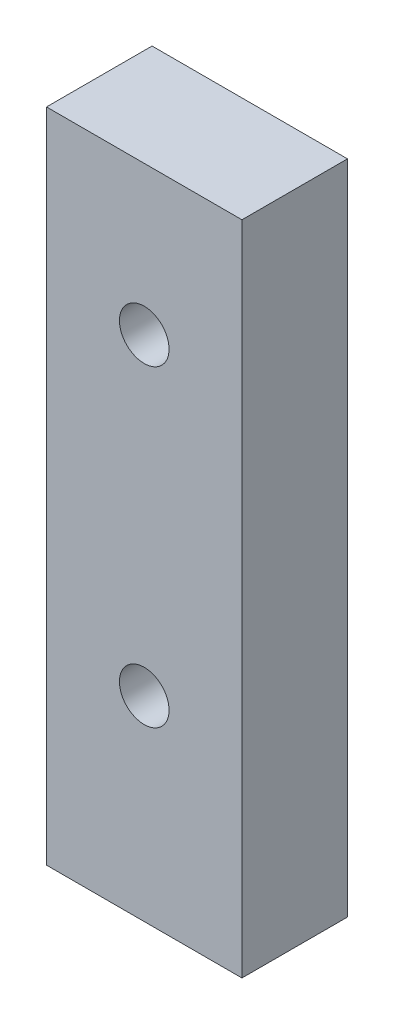
SolidWorks part; units mm, degrees
ref_plane "Alzado" through (0, 0, 0) normal (0, 0, 1) x (1, 0, 0)
ref_plane "Planta" through (0, 0, 0) normal (0, 1, 0) x (1, 0, 0)
ref_plane "Vista lateral" through (0, 0, 0) normal (1, 0, 0) x (0, 0, -1)
sketch "Sketch1" plane through (0, 0, 0) normal (0, 0, 1) x (1, 0, 0)
  line L1 (0, 0) -> (25, 0)
  line L2 (0, 0) -> (0, 84)
  line L3 (0, 84) -> (25, 84)
  line L4 (25, 0) -> (25, 84)
  dimension "D1" = 84
  dimension "D2" = 25
extrude "Boss-Extrude1" add sketch "Sketch1" along normal blind 13.5
sketch "Sketch2" plane through (0, 0, 13.5) normal (0, 0, 1) x (1, 0, 0)
  line L0 (12.5, 0) -> (12.5, 25) construction
  line L1 (12.5, 25) -> (12.5, 65) construction
  line L4 (0, 84) -> (0, 0)
  line L5 (0, 0) -> (25, 0)
  line L6 (25, 0) -> (25, 84)
  line L7 (25, 84) -> (0, 84)
  line L8 (0, 84) -> (0, 0)
  line L9 (0, 0) -> (25, 0)
  line L10 (25, 0) -> (25, 84)
  line L11 (25, 84) -> (0, 84)
  circle A0 centre (12.5, 65) radius 3.175
  circle A1 centre (12.5, 25) radius 3.175
  dimension "D4" = 6.35
  dimension "D5" = 6.35
  dimension "D2" = 25
  dimension "D3" = 40
  dimension "D1" = 0
extrude "Cut-Extrude1" cut sketch "Sketch2" against normal up to surface (13.5 mm away) contours A0 | A1 up to face at (12.5, 42, 0)
